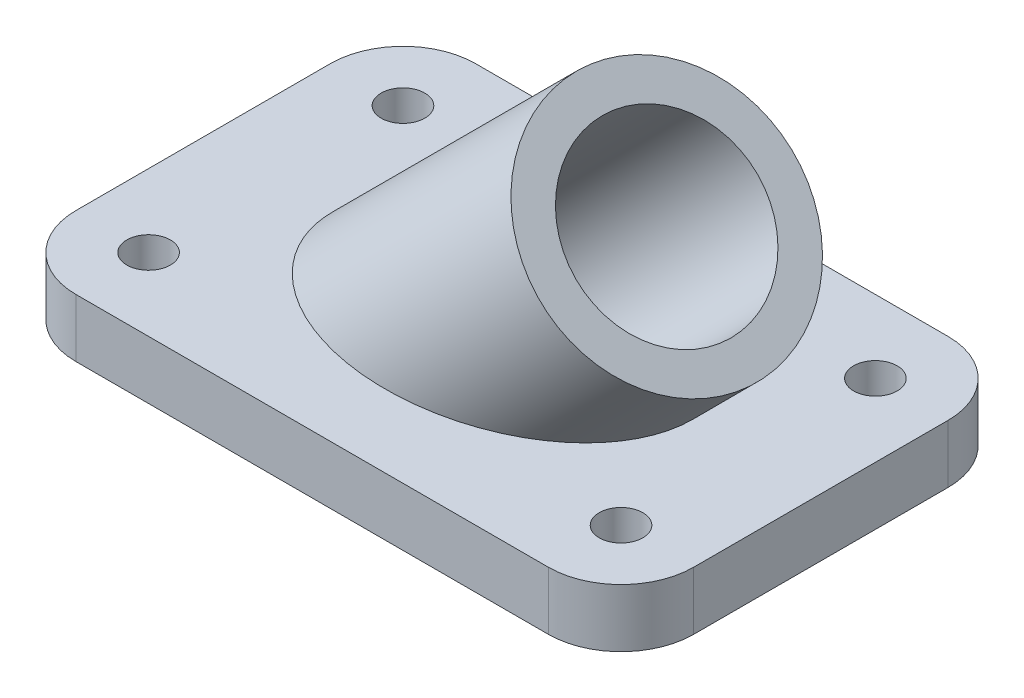
SolidWorks part; units mm, degrees
material "Gray Cast Iron"
ref_plane "Front Plane" through (0, 0, 0) normal (0, 0, 1) x (1, 0, 0)
ref_plane "Top Plane" through (0, 0, 0) normal (0, 1, 0) x (1, 0, 0)
ref_plane "Right Plane" through (0, 0, 0) normal (1, 0, 0) x (0, 0, -1)
sketch "Sketch1" plane through (0, 0, 0) normal (0, 1, 0) x (1, 0, 0)
  line L1 (-53.975, -34.925) -> (53.975, -34.925)
  line L2 (-53.975, -34.925) -> (-53.975, 34.925)
  line L3 (-53.975, 34.925) -> (53.975, 34.925)
  line L4 (53.975, -34.925) -> (53.975, 34.925)
  line L5 (-53.975, -34.925) -> (53.975, 34.925) construction
  line L6 (-53.975, 34.925) -> (53.975, -34.925) construction
  point P0 (0, 0)
  dimension "D1" = 107.95
  dimension "D2" = 69.85
extrude "Boss-Extrude1" add sketch "Sketch1" along normal blind 10.16
sketch "Sketch3" plane through (0, 10.16, 0) normal (0, 1, 0) x (1, 0, 0)
  line L0 (53.975, -34.925) -> (53.975, 34.925) construction
  circle A0 centre (41.275, 22.225) radius 3.81
  dimension "D2" = 7.62
  dimension "D1" = 12.7
  dimension "D3" = 12.7
extrude "Cut-Extrude1" cut sketch "Sketch3" against normal through all
pattern_linear "LPattern1" count 20 spacing 82.55 along (-1, 0, 0) count 2 spacing 44.45 along (0, 0, 1) of "Cut-Extrude1"
fillet "Fillet1" radius 12.7 4 edges at (-53.975, 5.08, -34.925) (53.975, 5.08, -34.925) (53.975, 5.08, 34.925) (-53.975, 5.08, 34.925)
ref_plane "Plane1" through (32.0675, 32.0675, 0) normal (0.7071, 0.7071, 0) x (0, 0, -1)
sketch "Sketch4" plane through (32.0675, 32.0675, 0) normal (0.7071, 0.7071, 0) x (0, 0, -1)
  line L0 (-22.225, -30.9819) -> (22.225, -30.9819) construction
  line L1 (34.925, -22.0016) -> (34.925, 36.37) construction
  circle A0 centre (0, 7.1181) radius 22.225
  dimension "D1" = 44.45
  dimension "D2" = 38.1
  dimension "D3" = 34.925
extrude "Boss-Extrude2" add sketch "Sketch4" against normal up to next
sketch "Sketch5" plane through (32.0675, 32.0675, 0) normal (0.7071, 0.7071, 0) x (0, 0, -1)
  circle A0 centre (0, 7.1181) radius 15.875
  circle A1 centre (0, 7.1181) radius 22.225 construction
  point P2 (0, 0)
  dimension "D1" = 31.75
extrude "Cut-Extrude2" cut sketch "Sketch5" against normal through all
